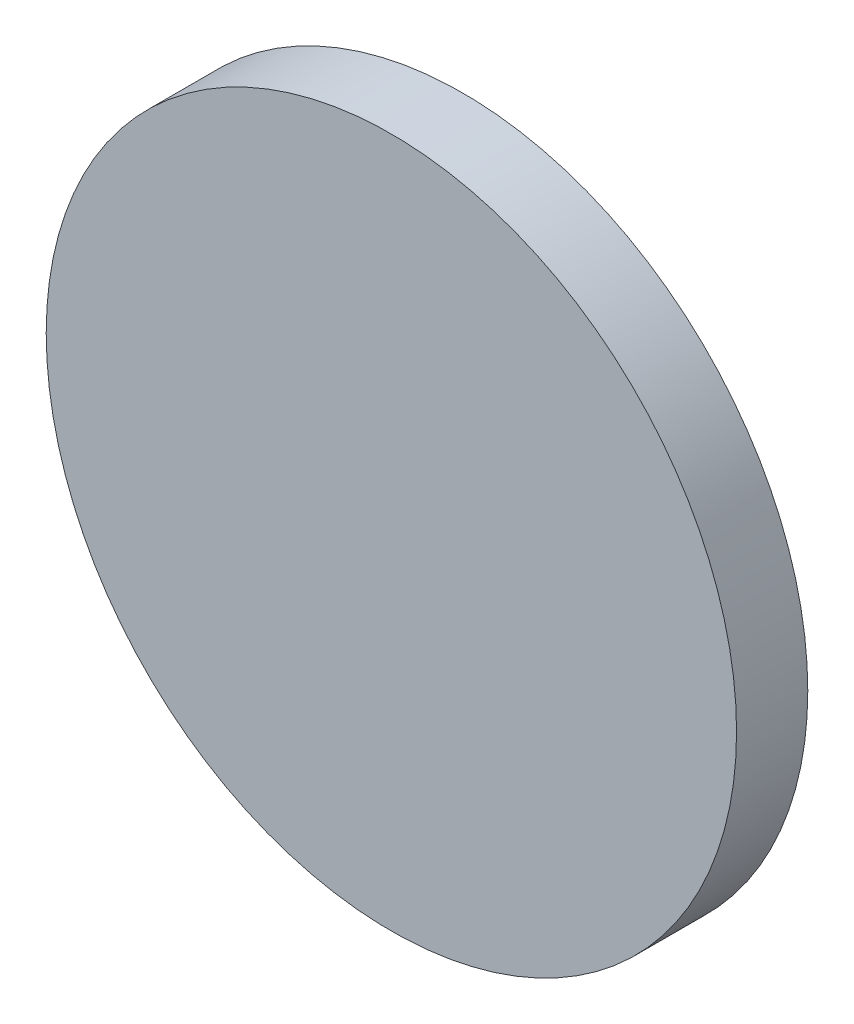
SolidWorks part; units mm, degrees
ref_plane "Front Plane" through (0, 0, 0) normal (0, 0, 1) x (1, 0, 0)
ref_plane "Top Plane" through (0, 0, 0) normal (0, 1, 0) x (1, 0, 0)
ref_plane "Right Plane" through (0, 0, 0) normal (1, 0, 0) x (0, 0, -1)
sketch "Sketch2" plane through (0, 0, 0) normal (0, 0, 1) x (1, 0, 0)
  circle A0 centre (0, 0) radius 16.002
  dimension "D1" = 32.004
extrude "Boss-Extrude2" add sketch "Sketch2" along normal blind 3.302
